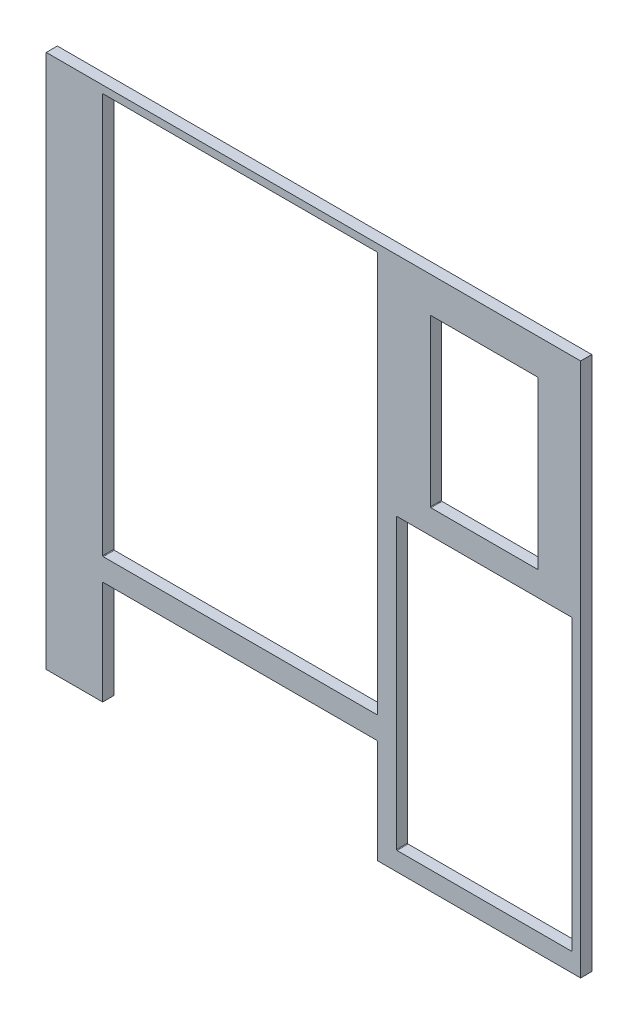
SolidWorks part; units mm, degrees
ref_plane "Front Plane" through (0, 0, 0) normal (0, 0, 1) x (1, 0, 0)
ref_plane "Top Plane" through (0, 0, 0) normal (0, 1, 0) x (1, 0, 0)
ref_plane "Right Plane" through (0, 0, 0) normal (1, 0, 0) x (0, 0, -1)
sketch "Sketch1" plane through (0, 0, 0) normal (0, 0, 1) x (1, 0, 0)
  line L1 (457.2, -457.2) -> (-457.2, -457.2)
  line L2 (457.2, -457.2) -> (457.2, 457.2)
  line L3 (457.2, 457.2) -> (-457.2, 457.2)
  line L4 (-457.2, -457.2) -> (-457.2, 457.2)
  line L5 (457.2, -457.2) -> (-457.2, 457.2) construction
  line L6 (457.2, 457.2) -> (-457.2, -457.2) construction
  point P0 (0, 0)
  dimension "D1" = 914.4
  dimension "D2" = 914.4
extrude "Boss-Extrude1" add sketch "Sketch1" along normal mid plane 19.05
sketch "Sketch2" plane through (0, 0, 9.525) normal (0, 0, 1) x (1, 0, 0)
  line L0 (292.1, 396.5) -> (292.1, 111.5) construction
  line L1 (200.1, 396.5) -> (384.1, 396.5)
  line L2 (200.1, 396.5) -> (200.1, 111.5)
  line L3 (200.1, 111.5) -> (384.1, 111.5)
  line L4 (384.1, 396.5) -> (384.1, 111.5)
  line L5 (142.1, 69.7) -> (442.1, 69.7)
  line L6 (142.1, 69.7) -> (142.1, -425.3)
  line L7 (142.1, -425.3) -> (442.1, -425.3)
  line L8 (442.1, 69.7) -> (442.1, -425.3)
  line L9 (-360.68, 444.5) -> (109.22, 444.5)
  line L10 (-360.68, 444.5) -> (-360.68, -241.3)
  line L11 (-360.68, -241.3) -> (109.22, -241.3)
  line L12 (109.22, 444.5) -> (109.22, -241.3)
  line L13 (200.1, 254) -> (384.1, 254) construction
  line L14 (292.1, 69.7) -> (292.1, -425.3) construction
  line L15 (142.1, -177.8) -> (442.1, -177.8) construction
  line L16 (-125.73, 444.5) -> (-125.73, -241.3) construction
  line L17 (-360.68, 101.6) -> (109.22, 101.6) construction
  line L18 (-125.73, -279.4) -> (-125.73, -241.3) construction
  line L19 (-360.68, -279.4) -> (109.22, -279.4)
  line L20 (-360.68, -279.4) -> (-360.68, -457.2)
  line L21 (-360.68, -457.2) -> (109.22, -457.2)
  line L22 (109.22, -279.4) -> (109.22, -457.2)
  line L23 (-360.68, -368.3) -> (109.22, -368.3) construction
  line L24 (-457.2, 457.2) -> (-457.2, -457.2) construction
  dimension "D1" = 292.1
  dimension "D2" = 300
  dimension "D3" = 96.52
  dimension "D4" = 184
  dimension "D5" = 495
  dimension "D6" = 177.8
  dimension "D7" = 254
  dimension "D8" = 285
  dimension "D9" = 685.8
  dimension "D10" = 101.6
  dimension "D11" = 469.9
  dimension "D13" = 177.8
  dimension "D14" = 368.3
extrude "Cut-Extrude1" cut sketch "Sketch2" against normal through all
fillet "Fillet1" radius 1 14 edges at (142.1, -425.3, 0) (142.1, 69.7, 0) (442.1, 69.7, 0) (442.1, -425.3, 0) (200.1, 111.5, 0) (384.1, 111.5, 0) (384.1, 396.5, 0) (200.1, 396.5, 0) (109.22, -279.4, 0) (-360.68, -279.4, 0) (-360.68, -241.3, 0) (109.22, -241.3, 0) (109.22, 444.5, 0) (-360.68, 444.5, 0)
